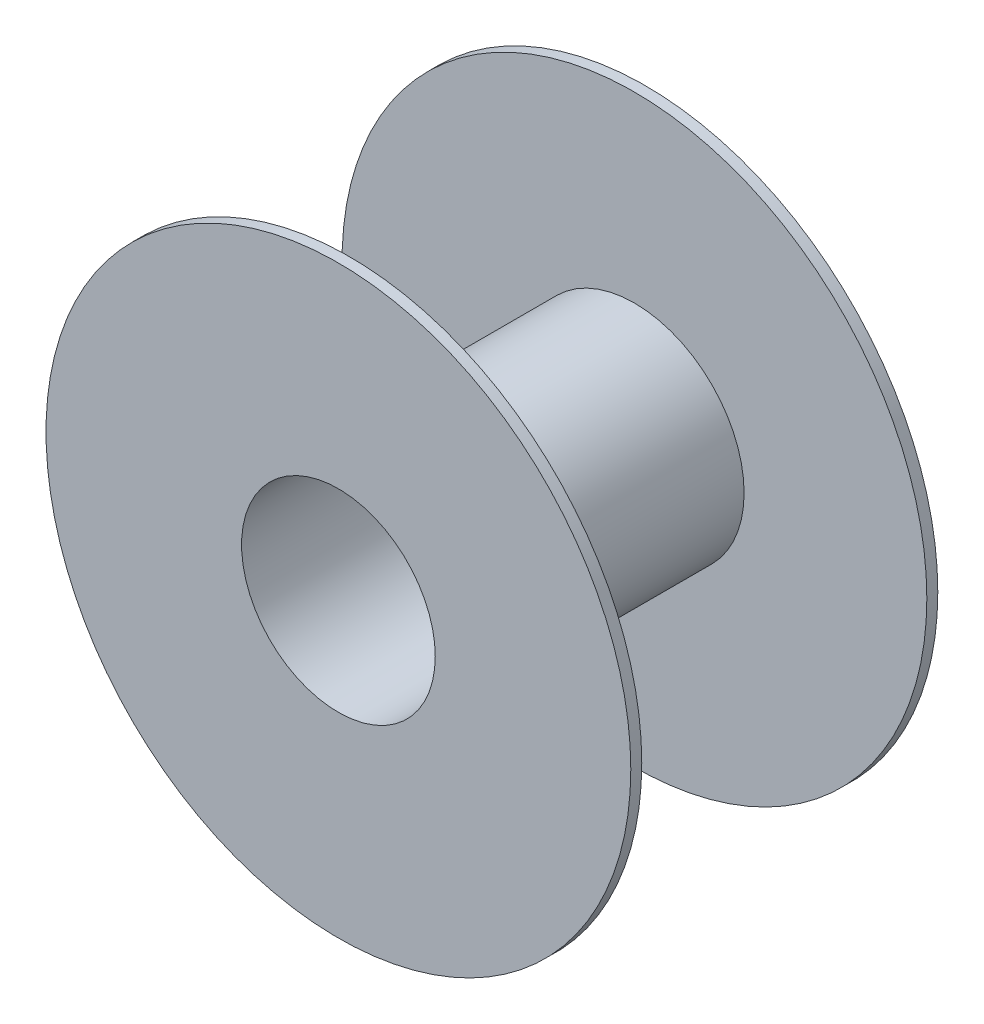
SolidWorks part; units mm, degrees
ref_plane "Front Plane" through (0, 0, 0) normal (0, 0, 1) x (1, 0, 0)
ref_plane "Top Plane" through (0, 0, 0) normal (0, 1, 0) x (1, 0, 0)
ref_plane "Right Plane" through (0, 0, 0) normal (1, 0, 0) x (0, 0, -1)
sketch "Sketch1" plane through (0, 0, 0) normal (0, 1, 0) x (1, 0, 0)
  line L0 (26.5, 0) -> (26.5, 84)
  line L1 (26.5, 84) -> (80, 84)
  line L2 (80, 84) -> (80, 81)
  line L3 (80, 81) -> (30, 81)
  line L4 (30, 81) -> (30, 3)
  line L5 (30, 3) -> (80, 3)
  line L6 (80, 3) -> (80, 0)
  line L7 (80, 0) -> (26.5, 0)
  line L8 (0, 0) -> (0, 63.518) construction
  dimension "D1" = 53
  dimension "D2" = 84
  dimension "D3" = 3
  dimension "D4" = 60
  dimension "D5" = 160
revolve "Revolve1" add sketch "Sketch1" angle 360 about L8
